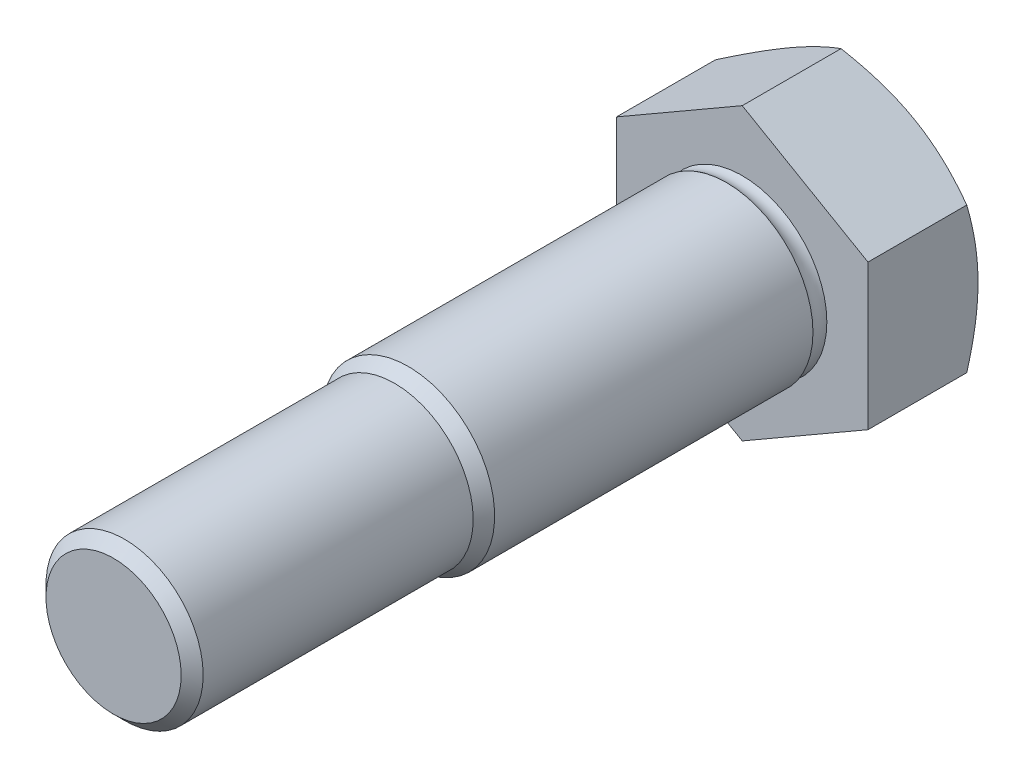
SolidWorks part; units mm, degrees
ref_plane "Přední rovina" through (0, 0, 0) normal (0, 0, 1) x (1, 0, 0)
ref_plane "Vrchní rovina" through (0, 0, 0) normal (0, 1, 0) x (1, 0, 0)
ref_plane "Pravá rovina" through (0, 0, 0) normal (1, 0, 0) x (0, 0, -1)
sketch "Skica1" plane through (0, 0, 0) normal (0, 0, 1) x (1, 0, 0)
  line L1 (8, -4.6188) -> (8, 4.6188)
  line L2 (8, 4.6188) -> (0, 9.2376)
  line L3 (0, 9.2376) -> (-8, 4.6188)
  line L4 (-8, 4.6188) -> (-8, -4.6188)
  line L5 (-8, -4.6188) -> (0, -9.2376)
  line L6 (0, -9.2376) -> (8, -4.6188)
  circle A0 centre (0, 0) radius 8 construction
  dimension "s" = 16
extrude "Vysunout1" add sketch "Skica1" along normal blind 7
sketch "Skica2" plane through (0, 0, 0) normal (0, 1, 0) x (1, 0, 0)
  line L0 (8, 0) -> (20.1244, 0)
  line L1 (20.1244, 0) -> (20.1244, -7)
  line L2 (20.1244, -7) -> (8, 0)
  line L3 (8, -7) -> (0, -7) construction
  line L4 (0, 0) -> (0, -7) construction
  dimension "D1" = 30
revolve "Odebrat otočením1" cut sketch "Skica2" angle 360 about L4
sketch "Skica5" plane through (0, 0, 7) normal (0, 0, 1) x (1, 0, 0)
  circle A0 centre (0, 0) radius 5
  dimension "M" = 10
extrude "Vysunout4" add sketch "Skica5" along normal blind 40
cosmetic thread "Kosmetický závit1" parameters "b"=16, "D2"=8.5
chamfer "Zkosit1" distance 0.7 angle 45 1 edges at (5, 0, 47)
sketch "Skica3" plane through (0, 0, 7) normal (0, 0, 1) x (1, 0, 0)
  circle A0 centre (0, 0) radius 5.3
  dimension "d3" = 10.6
extrude "Vysunout2" add sketch "Skica3" along normal blind 1
ref_plane "Rovina1" through (0, 0, 29.12) normal (0, 0, 1) x (1, 0, 0)
sketch "Skica4" plane through (0, 0, 8) normal (0, 0, 1) x (1, 0, 0)
  circle A0 centre (0, 0) radius 5.5
  dimension "d2" = 11
extrude "Vysunout3" add sketch "Skica4" along normal up to surface (21.12 mm away) up to plane "Rovina1"
sketch "Skica6" plane through (0, 0, 0) normal (0, 1, 0) x (1, 0, 0)
  line L0 (-5.5, -29.12) -> (-5.5, -28.254)
  line L1 (-5.5, -28.254) -> (-5, -29.12)
  line L2 (-5, -29.12) -> (-5.5, -29.12)
  line L3 (0, -29.12) -> (0, -8) construction
  line L4 (-5.5, -29.12) -> (5.5, -29.12) construction
  line L5 (5.5, -8) -> (-5.5, -8) construction
  dimension "D1" = 30
revolve "Odebrat otočením2" cut sketch "Skica6" angle 360 about L3
sketch "Skica7" plane through (0, 0, 0) normal (0, 1, 0) x (1, 0, 0)
  line L0 (8, -7) -> (0, -7) construction
  line L1 (5.3, -8) -> (5.3, -7) construction
  line L2 (5.3835, -7) -> (5.3, -7)
  line L3 (5.3, -7) -> (5.3, -8)
  line L4 (5.5, -8) -> (-5.5, -8) construction
  line L5 (5.3, -8) -> (5.5, -8)
  line L6 (0, -28.254) -> (0, -8) construction
  line L7 (5.5, -28.254) -> (-5.5, -28.254) construction
  arc A0 (5.5, -8) -> (5.3835, -7) centre (6.3, -7.4) cw
  dimension "D1" = 1
revolve "Otočit kolem osy1" add sketch "Skica7" angle 360 about L6
equation "\"D1@Zkosit1\" = 0.07 * \"M@Skica5\""
equation "\"D1@Skica7\" = \"r@Vysunout2\""
equation "\"D2@Kosmetický závit1\" = 0.85 * \"M@Skica5\""
